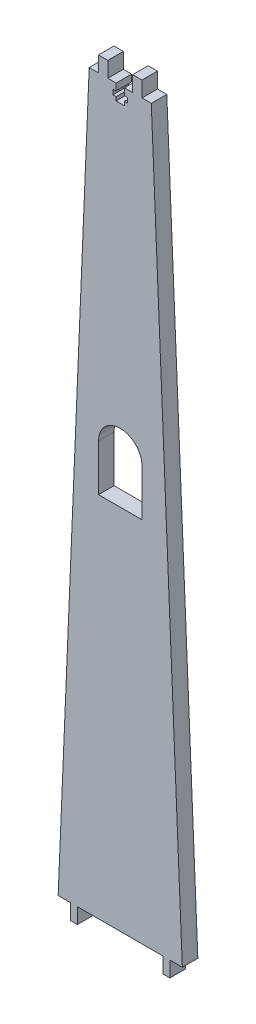
SolidWorks part; units mm, degrees
ref_plane "Front Plane" through (0, 0, 0) normal (0, 0, 1) x (1, 0, 0)
ref_plane "Top Plane" through (0, 0, 0) normal (0, 1, 0) x (1, 0, 0)
ref_plane "Right Plane" through (0, 0, 0) normal (1, 0, 0) x (0, 0, -1)
sketch "Sketch1" plane through (0, 0, 0) normal (0, 0, 1) x (1, 0, 0)
  line L1 (25.4, 0) -> (12.7, 299.72)
  line L3 (-12.7, 299.72) -> (-25.4, 0)
  line L4 (0, 0) -> (0, 299.72) construction
  line L5 (-25.4, 0) -> (-20.32, 0)
  line L6 (-20.32, 0) -> (-20.32, -6.35)
  line L7 (-20.32, -6.35) -> (-17.526, -6.35)
  line L8 (-17.526, -6.35) -> (-17.526, 0)
  line L9 (-17.526, 0) -> (17.526, 0)
  line L10 (25.4, 0) -> (20.32, 0)
  line L11 (17.526, -6.35) -> (17.526, 0)
  line L12 (20.32, -6.35) -> (17.526, -6.35)
  line L13 (20.32, 0) -> (20.32, -6.35)
  line L14 (8.89, 306.07) -> (8.89, 299.72)
  line L15 (-12.7, 299.72) -> (-8.89, 299.72)
  line L16 (-8.89, 306.07) -> (-5.08, 306.07)
  line L17 (-8.89, 306.07) -> (-8.89, 299.72)
  line L18 (-5.08, 306.07) -> (-5.08, 299.72)
  line L19 (-5.08, 299.72) -> (-1.7, 299.72)
  line L20 (-1.7, 299.72) -> (-1.7, 296.926)
  line L21 (-1.7, 296.926) -> (-2.97, 296.926)
  line L22 (-2.97, 296.926) -> (-2.97, 294.894)
  line L23 (12.7, 299.72) -> (8.89, 299.72)
  line L24 (-2.97, 294.894) -> (-1.7, 294.894)
  line L25 (8.89, 306.07) -> (5.08, 306.07)
  line L26 (5.08, 306.07) -> (5.08, 299.72)
  line L27 (5.08, 299.72) -> (1.7, 299.72)
  line L28 (1.7, 299.72) -> (1.7, 296.926)
  line L29 (1.7, 296.926) -> (2.97, 296.926)
  line L30 (2.97, 296.926) -> (2.97, 294.894)
  line L31 (2.97, 294.894) -> (1.7, 294.894)
  line L32 (1.7, 294.894) -> (1.7, 293.37)
  line L33 (1.7, 293.37) -> (-1.7, 293.37)
  line L34 (-1.7, 294.894) -> (-1.7, 293.37)
  line L35 (-8.89, 150.2972) -> (8.89, 150.2972)
  line L36 (8.89, 169.3472) -> (8.89, 150.2972)
  line L37 (-8.89, 169.3472) -> (-8.89, 150.2972)
  arc A0 (-8.89, 169.3472) -> (8.89, 169.3472) centre (0, 169.3472) cw
  point P37 (0, 293.37)
  point P41 (0, 0)
  dimension "D1" = 6.35
  dimension "D2" = 25.4
  dimension "D3" = 50.8
  dimension "D4" = 2.794
  dimension "D5" = 5.08
  dimension "D6" = 6.35
  dimension "D7" = 299.72
  dimension "D8" = 6.35
  dimension "D9" = 3.81
  dimension "D10" = 3.81
  dimension "D11" = 3.4
  dimension "D12" = 1.7
  dimension "D13" = 1.27
  dimension "D14" = 1.27
  dimension "D15" = 2.032
  dimension "D16" = 6.35
  dimension "D17" = 2.794
  dimension "D18" = 17.78
  dimension "D19" = 3.81
  dimension "D20" = 2.794
  dimension "D21" = 19.05
  dimension "D22" = 18.2079
extrude "Boss-Extrude1" add sketch "Sketch1" along normal blind 6.35
